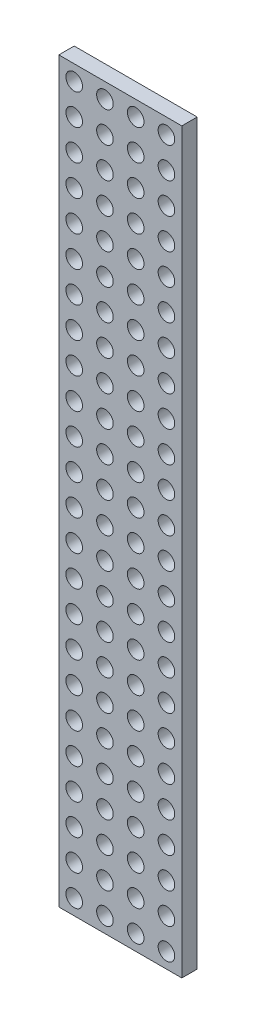
SolidWorks part; units mm, degrees
ref_plane "Front Plane" through (0, 0, 0) normal (0, 0, 1) x (1, 0, 0)
ref_plane "Top Plane" through (0, 0, 0) normal (0, 1, 0) x (1, 0, 0)
ref_plane "Right Plane" through (0, 0, 0) normal (1, 0, 0) x (0, 0, -1)
sketch "Sketch1" plane through (0, 0, 0) normal (0, 0, 1) x (1, 0, 0)
  line L1 (0, 0) -> (50.8, 0)
  line L2 (0, 0) -> (0, -304.8)
  line L3 (0, -304.8) -> (50.8, -304.8)
  line L4 (50.8, 0) -> (50.8, -304.8)
  dimension "D1" = 50.8
  dimension "D2" = 304.8
extrude "Boss-Extrude1" add sketch "Sketch1" along normal blind 6.35
sketch "Sketch2" plane through (0, 0, 0) normal (0, 0, 1) x (1, 0, 0)
  line L0 (50.8, 0) -> (0, 0) construction
  line L2 (0, 0) -> (0, -304.8) construction
  circle A0 centre (6.35, -6.35) radius 3.429
  circle A1 centre (19.05, -6.35) radius 3.429
  circle A2 centre (31.75, -6.35) radius 3.429
  circle A3 centre (44.45, -6.35) radius 3.429
  circle A4 centre (19.05, -19.05) radius 3.429
  circle A5 centre (31.75, -19.05) radius 3.429
  circle A6 centre (44.45, -19.05) radius 3.429
  circle A7 centre (19.05, -31.75) radius 3.429
  circle A8 centre (31.75, -31.75) radius 3.429
  circle A9 centre (44.45, -31.75) radius 3.429
  circle A10 centre (19.05, -44.45) radius 3.429
  circle A11 centre (31.75, -44.45) radius 3.429
  circle A12 centre (44.45, -44.45) radius 3.429
  circle A13 centre (19.05, -57.15) radius 3.429
  circle A14 centre (31.75, -57.15) radius 3.429
  circle A15 centre (44.45, -57.15) radius 3.429
  circle A16 centre (19.05, -69.85) radius 3.429
  circle A17 centre (31.75, -69.85) radius 3.429
  circle A18 centre (44.45, -69.85) radius 3.429
  circle A19 centre (19.05, -82.55) radius 3.429
  circle A20 centre (31.75, -82.55) radius 3.429
  circle A21 centre (44.45, -82.55) radius 3.429
  circle A22 centre (19.05, -95.25) radius 3.429
  circle A23 centre (31.75, -95.25) radius 3.429
  circle A24 centre (44.45, -95.25) radius 3.429
  circle A25 centre (19.05, -107.95) radius 3.429
  circle A26 centre (31.75, -107.95) radius 3.429
  circle A27 centre (44.45, -107.95) radius 3.429
  circle A28 centre (19.05, -120.65) radius 3.429
  circle A29 centre (31.75, -120.65) radius 3.429
  circle A30 centre (44.45, -120.65) radius 3.429
  circle A31 centre (19.05, -133.35) radius 3.429
  circle A32 centre (31.75, -133.35) radius 3.429
  circle A33 centre (44.45, -133.35) radius 3.429
  circle A34 centre (19.05, -146.05) radius 3.429
  circle A35 centre (31.75, -146.05) radius 3.429
  circle A36 centre (44.45, -146.05) radius 3.429
  circle A37 centre (19.05, -158.75) radius 3.429
  circle A38 centre (31.75, -158.75) radius 3.429
  circle A39 centre (44.45, -158.75) radius 3.429
  circle A40 centre (19.05, -171.45) radius 3.429
  circle A41 centre (31.75, -171.45) radius 3.429
  circle A42 centre (44.45, -171.45) radius 3.429
  circle A43 centre (19.05, -184.15) radius 3.429
  circle A44 centre (31.75, -184.15) radius 3.429
  circle A45 centre (44.45, -184.15) radius 3.429
  circle A46 centre (19.05, -196.85) radius 3.429
  circle A47 centre (31.75, -196.85) radius 3.429
  circle A48 centre (44.45, -196.85) radius 3.429
  circle A49 centre (19.05, -209.55) radius 3.429
  circle A50 centre (31.75, -209.55) radius 3.429
  circle A51 centre (44.45, -209.55) radius 3.429
  circle A52 centre (19.05, -222.25) radius 3.429
  circle A53 centre (31.75, -222.25) radius 3.429
  circle A54 centre (44.45, -222.25) radius 3.429
  circle A55 centre (19.05, -234.95) radius 3.429
  circle A56 centre (31.75, -234.95) radius 3.429
  circle A57 centre (44.45, -234.95) radius 3.429
  circle A58 centre (19.05, -247.65) radius 3.429
  circle A59 centre (31.75, -247.65) radius 3.429
  circle A60 centre (44.45, -247.65) radius 3.429
  circle A61 centre (19.05, -260.35) radius 3.429
  circle A62 centre (31.75, -260.35) radius 3.429
  circle A63 centre (44.45, -260.35) radius 3.429
  circle A64 centre (19.05, -273.05) radius 3.429
  circle A65 centre (31.75, -273.05) radius 3.429
  circle A66 centre (44.45, -273.05) radius 3.429
  circle A67 centre (19.05, -285.75) radius 3.429
  circle A68 centre (31.75, -285.75) radius 3.429
  circle A69 centre (44.45, -285.75) radius 3.429
  circle A70 centre (19.05, -298.45) radius 3.429
  circle A71 centre (31.75, -298.45) radius 3.429
  circle A72 centre (44.45, -298.45) radius 3.429
  circle A73 centre (19.05, -311.15) radius 3.429
  circle A74 centre (31.75, -311.15) radius 3.429
  circle A75 centre (44.45, -311.15) radius 3.429
  circle A76 centre (19.05, -323.85) radius 3.429
  circle A77 centre (31.75, -323.85) radius 3.429
  circle A78 centre (44.45, -323.85) radius 3.429
  circle A79 centre (19.05, -336.55) radius 3.429
  circle A80 centre (31.75, -336.55) radius 3.429
  circle A81 centre (44.45, -336.55) radius 3.429
  circle A82 centre (19.05, -349.25) radius 3.429
  circle A83 centre (31.75, -349.25) radius 3.429
  circle A84 centre (44.45, -349.25) radius 3.429
  circle A85 centre (19.05, -361.95) radius 3.429
  circle A86 centre (31.75, -361.95) radius 3.429
  circle A87 centre (44.45, -361.95) radius 3.429
  circle A88 centre (19.05, -374.65) radius 3.429
  circle A89 centre (31.75, -374.65) radius 3.429
  circle A90 centre (44.45, -374.65) radius 3.429
  circle A91 centre (6.35, -19.05) radius 3.429
  circle A92 centre (6.35, -31.75) radius 3.429
  circle A93 centre (6.35, -44.45) radius 3.429
  circle A94 centre (6.35, -57.15) radius 3.429
  circle A95 centre (6.35, -69.85) radius 3.429
  circle A96 centre (6.35, -82.55) radius 3.429
  circle A97 centre (6.35, -95.25) radius 3.429
  circle A98 centre (6.35, -107.95) radius 3.429
  circle A99 centre (6.35, -120.65) radius 3.429
  circle A100 centre (6.35, -133.35) radius 3.429
  circle A101 centre (6.35, -146.05) radius 3.429
  circle A102 centre (6.35, -158.75) radius 3.429
  circle A103 centre (6.35, -171.45) radius 3.429
  circle A104 centre (6.35, -184.15) radius 3.429
  circle A105 centre (6.35, -196.85) radius 3.429
  circle A106 centre (6.35, -209.55) radius 3.429
  circle A107 centre (6.35, -222.25) radius 3.429
  circle A108 centre (6.35, -234.95) radius 3.429
  circle A109 centre (6.35, -247.65) radius 3.429
  circle A110 centre (6.35, -260.35) radius 3.429
  circle A111 centre (6.35, -273.05) radius 3.429
  circle A112 centre (6.35, -285.75) radius 3.429
  circle A113 centre (6.35, -298.45) radius 3.429
  circle A114 centre (6.35, -311.15) radius 3.429
  circle A115 centre (6.35, -323.85) radius 3.429
  circle A116 centre (6.35, -336.55) radius 3.429
  circle A117 centre (6.35, -349.25) radius 3.429
  circle A118 centre (6.35, -361.95) radius 3.429
  circle A119 centre (6.35, -374.65) radius 3.429
  dimension "D1" = 6.858
  dimension "D2" = 6.35
  dimension "D3" = 6.35
  dimension "D4" = 4
  dimension "D5" = 30
extrude "Cut-Extrude1" cut sketch "Sketch2" along normal through all
